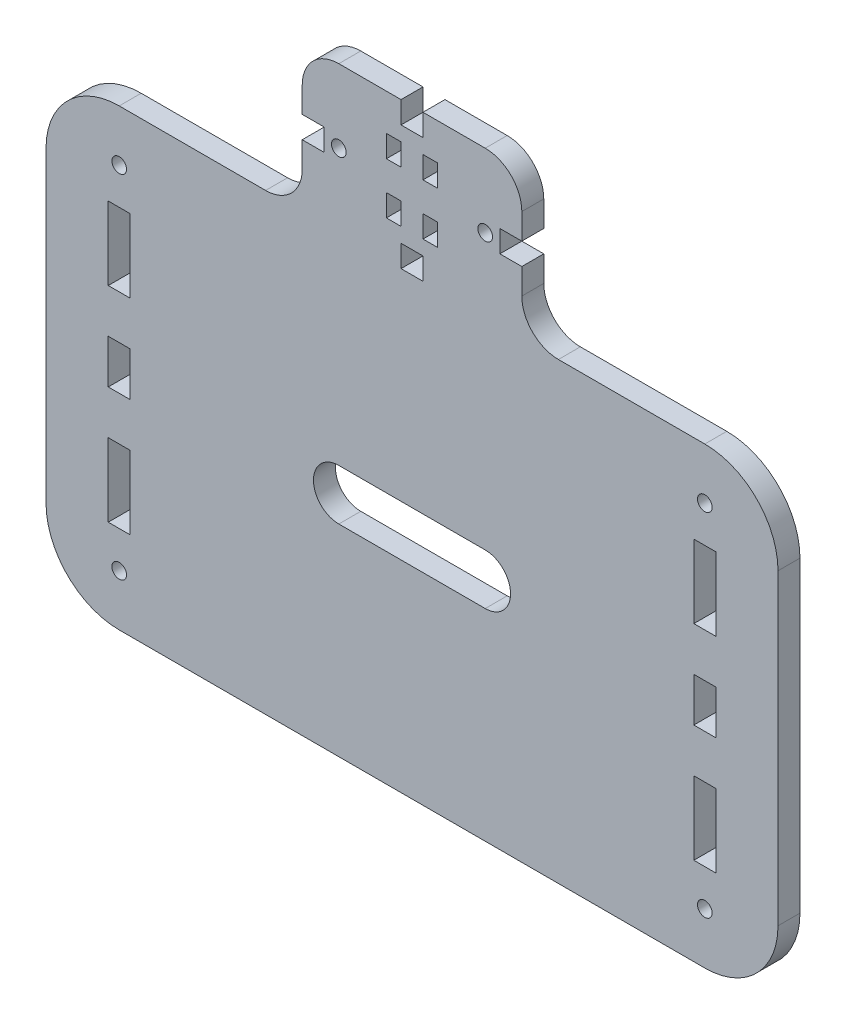
SolidWorks part; units mm, degrees
ref_plane "Plan de face" through (0, 0, 0) normal (0, 0, 1) x (1, 0, 0)
ref_plane "Plan de dessus" through (0, 0, 0) normal (0, 1, 0) x (1, 0, 0)
ref_plane "Plan de droite" through (0, 0, 0) normal (1, 0, 0) x (0, 0, -1)
sketch "Esquisse1" plane through (0, 0, 0) normal (0, 0, 1) x (1, 0, 0)
  line L0 (-200, 155) -> (-200, -155) construction
  line L1 (-200, -155) -> (200, -155)
  line L2 (-250, -105) -> (-250, 105)
  line L3 (-200, 155) -> (-100, 155)
  line L4 (250, -105) -> (250, 105)
  line L5 (-250, -155) -> (250, 155) construction
  line L6 (-250, 155) -> (250, -155) construction
  line L7 (200, 155) -> (200, -155) construction
  line L8 (192.5, -15) -> (207.5, -15)
  line L9 (-250, 105) -> (250, 105) construction
  line L10 (250, -105) -> (-250, -105) construction
  line L11 (250, 0) -> (-250, 0) construction
  line L12 (192.5, 95) -> (207.5, 95)
  line L13 (192.5, 95) -> (192.5, 45)
  line L14 (192.5, 45) -> (207.5, 45)
  line L15 (207.5, 95) -> (207.5, 45)
  line L16 (192.5, 95) -> (207.5, 45) construction
  line L17 (192.5, 45) -> (207.5, 95) construction
  line L18 (192.5, 15) -> (207.5, 15)
  line L19 (192.5, 15) -> (192.5, -15)
  line L20 (0, 155) -> (0, -155) construction
  line L21 (207.5, 15) -> (207.5, -15)
  line L22 (192.5, 15) -> (207.5, 0) construction
  line L23 (192.5, 0) -> (207.5, 15) construction
  line L24 (192.5, -45) -> (207.5, -45)
  line L25 (192.5, -95) -> (192.5, -45)
  line L26 (192.5, -95) -> (207.5, -95)
  line L27 (207.5, -95) -> (207.5, -45)
  line L28 (-192.5, -95) -> (-207.5, -95)
  line L29 (-192.5, -95) -> (-192.5, -45)
  line L30 (-207.5, -95) -> (-207.5, -45)
  line L31 (-192.5, -45) -> (-207.5, -45)
  line L32 (-192.5, -15) -> (-207.5, -15)
  line L33 (-192.5, 15) -> (-207.5, 15)
  line L34 (-192.5, 15) -> (-192.5, -15)
  line L35 (-207.5, 15) -> (-207.5, -15)
  line L36 (-192.5, 45) -> (-207.5, 45)
  line L37 (-192.5, 95) -> (-207.5, 95)
  line L38 (-207.5, 95) -> (-207.5, 45)
  line L39 (-192.5, 95) -> (-192.5, 45)
  line L40 (0, 255) -> (0, 155) construction
  line L41 (75, 180) -> (75, 230)
  line L42 (50, 255) -> (-50, 255)
  line L43 (-75, 230) -> (-75, 180)
  line L44 (100, 155) -> (200, 155)
  line L45 (-75, 205) -> (75, 205) construction
  line L46 (50, 0) -> (-50, 0) construction
  line L47 (50, -17.3213) -> (-50, -17.3213)
  line L48 (50, 17.3213) -> (-50, 17.3213)
  arc A0 (-200, -155) -> (-250, -105) centre (-200, -105) cw
  arc A1 (200, -155) -> (250, -105) centre (200, -105) ccw
  arc A2 (250, 105) -> (200, 155) centre (200, 105) ccw
  arc A3 (-250, 105) -> (-200, 155) centre (-200, 105) cw
  circle A4 centre (200, 120) radius 5
  circle A5 centre (200, -120) radius 5
  circle A6 centre (-200, -120) radius 5
  circle A7 centre (-200, 120) radius 5
  arc A8 (-75, 230) -> (-50, 255) centre (-50, 230) cw
  arc A9 (50, 255) -> (75, 230) centre (50, 230) cw
  arc A10 (100, 155) -> (75, 180) centre (100, 180) cw
  arc A11 (-100, 155) -> (-75, 180) centre (-100, 180) ccw
  arc A12 (50, -17.3213) -> (50, 17.3213) centre (50, 0) ccw
  arc A13 (-50, 17.3213) -> (-50, -17.3213) centre (-50, 0) ccw
  point P0 (0, 0)
  point P22 (200, 70)
  point P27 (200, 7.5)
  point P61 (0, 155)
  point P67 (75, 255)
  point P70 (75, 155)
  point P73 (-75, 155)
  point P79 (0, 0)
  dimension "D3" = 50
  dimension "D5" = 10
  dimension "D13" = 25
  dimension "D1" = 500
  dimension "D2" = 310
  dimension "D4" = 35
  dimension "D6" = 60
  dimension "D7" = 15
  dimension "D8" = 50
  dimension "D9" = 30
  dimension "D10" = 15
  dimension "D11" = 150
  dimension "D12" = 100
  dimension "D14" = 100
extrude "Boss.-Extru.1" add sketch "Esquisse1" along normal blind 15
sketch "Esquisse2" plane through (0, 0, 15) normal (0, 0, 1) x (1, 0, 0)
  line L0 (0, 155) -> (0, 255) construction
  line L1 (50, 255) -> (-50, 255) construction
  line L2 (75, 205) -> (-75, 205) construction
  line L3 (75, 180) -> (75, 230) construction
  line L4 (-75, 230) -> (-75, 180) construction
  line L5 (-100, 155) -> (100, 155) construction
  line L6 (-100, 155) -> (-200, 155) construction
  line L7 (94.8879, 212.5) -> (60, 212.5)
  line L8 (94.8879, 212.5) -> (94.8879, 197.5)
  line L9 (60, 212.5) -> (60, 197.5)
  line L10 (94.8879, 197.5) -> (60, 197.5)
  line L11 (-7.5, 240) -> (7.5, 240)
  line L12 (-7.5, 240) -> (-7.5, 255)
  line L13 (7.5, 240) -> (7.5, 255)
  line L14 (-7.5, 255) -> (7.5, 255)
  line L15 (-94.8879, 212.5) -> (-94.8879, 197.5)
  line L16 (-94.8879, 212.5) -> (-60, 212.5)
  line L17 (-60, 212.5) -> (-60, 197.5)
  line L18 (-94.8879, 197.5) -> (-60, 197.5)
  line L19 (-7.5, 155) -> (7.5, 155)
  line L20 (-7.5, 170) -> (-7.5, 155)
  line L21 (7.5, 170) -> (7.5, 155)
  line L22 (-7.5, 170) -> (7.5, 170)
  line L23 (7.5, 230) -> (7.5, 215)
  line L24 (7.5, 230) -> (17.5, 230)
  line L25 (7.5, 215) -> (17.5, 215)
  line L26 (17.5, 230) -> (17.5, 215)
  line L27 (-7.5, 215) -> (-17.5, 215)
  line L28 (-17.5, 230) -> (-17.5, 215)
  line L29 (-7.5, 230) -> (-7.5, 215)
  line L30 (-7.5, 230) -> (-17.5, 230)
  line L31 (17.5, 180) -> (17.5, 195)
  line L32 (7.5, 195) -> (17.5, 195)
  line L33 (7.5, 180) -> (7.5, 195)
  line L34 (7.5, 180) -> (17.5, 180)
  line L35 (-7.5, 180) -> (-17.5, 180)
  line L36 (-17.5, 180) -> (-17.5, 195)
  line L37 (-7.5, 195) -> (-17.5, 195)
  line L38 (-7.5, 180) -> (-7.5, 195)
  arc A0 (-100, 155) -> (-75, 180) centre (-100, 180) ccw construction
  circle A1 centre (50, 205) radius 5
  circle A2 centre (-50, 205) radius 5
  dimension "D8" = 10
  dimension "D1" = 15
  dimension "D2" = 15
  dimension "D3" = 7.5
  dimension "D4" = 15
  dimension "D5" = 7.5
  dimension "D6" = 15
  dimension "D7" = 15
  dimension "D9" = 10
  dimension "D10" = 15
  dimension "D11" = 10
  dimension "D12" = 10
extrude "Enlèv. mat.-Extru.1" cut sketch "Esquisse2" against normal through all
